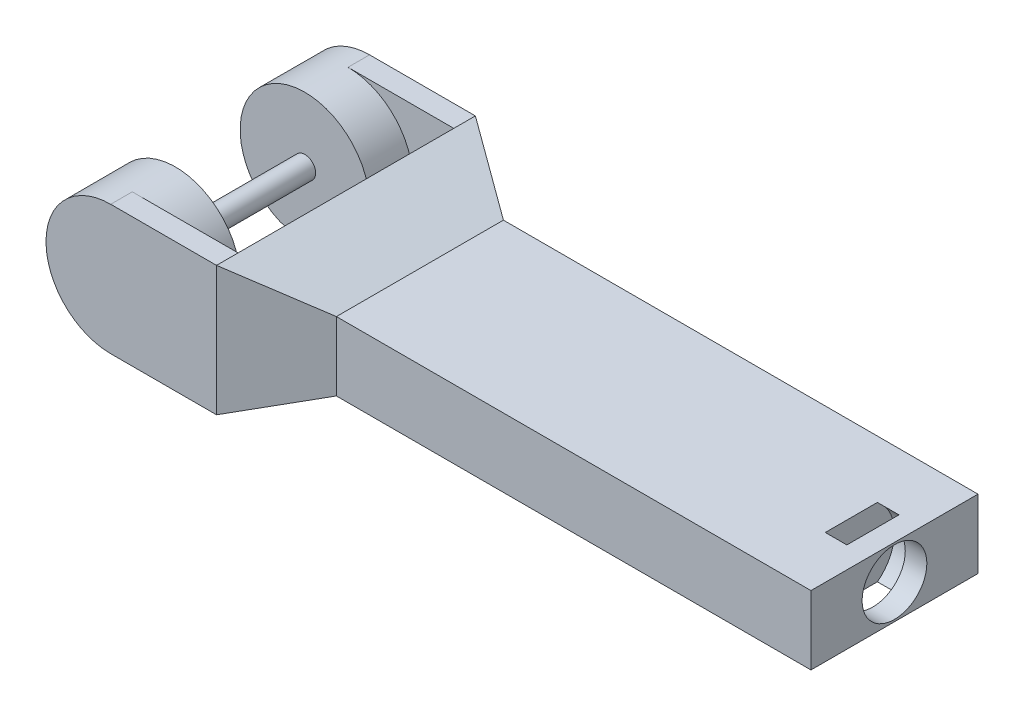
SolidWorks part; units mm, degrees
ref_plane "Front Plane" through (0, 0, 0) normal (0, 0, 1) x (1, 0, 0)
ref_plane "Top Plane" through (0, 0, 0) normal (0, 1, 0) x (1, 0, 0)
ref_plane "Right Plane" through (0, 0, 0) normal (1, 0, 0) x (0, 0, -1)
sketch "Sketch1" plane through (0, 0, 0) normal (0, 0, 1) x (1, 0, 0)
  circle A0 centre (0, 0) radius 5
  dimension "D1" = 10
extrude "Boss-Extrude1" add sketch "Sketch1" along normal mid plane 60
sketch "Sketch2" plane through (0, 0, 30) normal (0, 0, 1) x (1, 0, 0)
  circle A0 centre (0, 0) radius 30
  dimension "D1" = 60
extrude "Boss-Extrude2" add sketch "Sketch2" along normal blind 20
mirror "Mirror1" about plane through (0, 0, 0) normal (0, 0, 1) of "Boss-Extrude2"
sketch "Sketch5" plane through (0, 0, 50) normal (0, 0, 1) x (1, 0, 0)
  line L0 (49.0469, 30) -> (49.0469, -30)
  line L1 (0, -30) -> (49.0469, -30)
  line L2 (0, 30) -> (49.0469, 30)
  circle A1 centre (0, 0) radius 30
  arc A2 (0, 30) -> (0, -30) centre (0, 0) ccw
  dimension "D1" = 0
extrude "Boss-Extrude3" add sketch "Sketch5" along normal blind 10
mirror "Mirror3" about plane through (0, 0, 0) normal (0, 0, 1) of "Boss-Extrude3"
sketch "Sketch6" plane through (0, 0, 0) normal (0, 0, 1) x (1, 0, 0)
  line L0 (42.0872, 0) -> (83.3346, 0) construction
  line L1 (49.0469, -30) -> (49.0469, 30)
  line L2 (49.0469, -30) -> (49.0469, 30) construction
  line L3 (49.0469, 30) -> (83.3346, 15.9427)
  line L4 (83.3346, 15.9427) -> (83.3346, -15.9427)
  line L5 (49.0469, -30) -> (83.3346, -15.9427)
  point P11 (49.0469, 0)
extrude "Boss-Extrude4" add sketch "Sketch6" along normal mid plane 120
sketch "Sketch7" plane through (0, 0, 0) normal (0, 1, 0) x (1, 0, 0)
  line L0 (49.0469, 60) -> (92.2408, 33.1866)
extrude "Cut-Extrude2" cut sketch "Sketch7" against normal through all and the other way through all
mirror "Mirror4" about plane through (0, 0, 0) normal (0, 0, 1) of "Cut-Extrude2"
sketch "Schizzo1" plane through (83.3346, 0, 0) normal (1, 0, 0) x (0, 0, -1)
  line L1 (-38.7153, 15.9427) -> (38.7153, 15.9427)
  line L2 (-38.7153, 15.9427) -> (-38.7153, -15.9427)
  line L3 (-38.7153, -15.9427) -> (38.7153, -15.9427)
  line L4 (38.7153, 15.9427) -> (38.7153, -15.9427)
extrude "Estrusione-Estrusione1" add sketch "Schizzo1" along normal blind 220
sketch "Sketch8" plane through (303.3346, 0, 0) normal (1, 0, 0) x (0, 0, -1)
  circle A0 centre (0, 0) radius 15
  dimension "D1" = 30
extrude "Cut-Extrude3" cut sketch "Sketch8" against normal blind 10
sketch "Sketch9" plane through (293.3346, 0, 0) normal (1, 0, 0) x (0, 0, -1)
  circle A2 centre (0, 0) radius 20
  circle A3 centre (0, 0) radius 20
  dimension "D1" = 5
extrude "Cut-Extrude4" cut sketch "Sketch9" against normal blind 10
